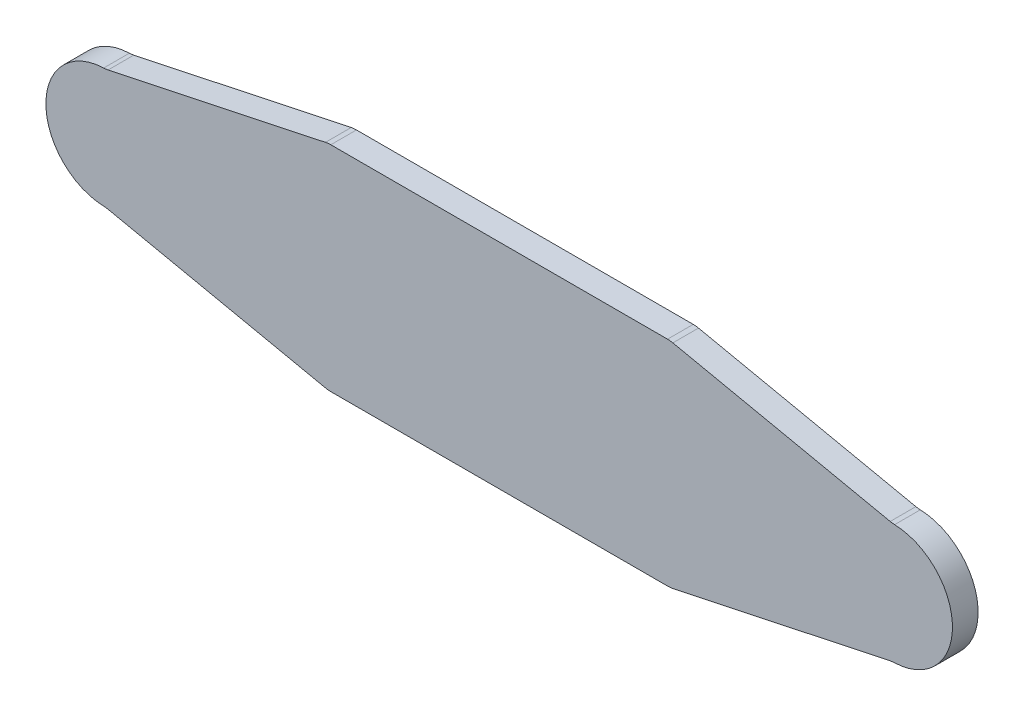
SolidWorks part; units mm, degrees
ref_plane "Front Plane" through (0, 0, 0) normal (0, 0, 1) x (1, 0, 0)
ref_plane "Top Plane" through (0, 0, 0) normal (0, 1, 0) x (1, 0, 0)
ref_plane "Right Plane" through (0, 0, 0) normal (1, 0, 0) x (0, 0, -1)
sketch "Sketch1" plane through (0, 0, 0) normal (0, 0, 1) x (1, 0, 0)
  line L0 (0, 0) -> (40, 0)
  line L1 (0, -25) -> (40, -25)
  line L2 (40, -25) -> (66, -19.5)
  line L3 (40, 0) -> (66, -5.5)
  line L4 (0, 0) -> (-26, -5.5)
  line L5 (0, -25) -> (-26, -19.5)
  arc A0 (-26, -5.5) -> (-26, -19.5) centre (-26, -12.5) ccw
  arc A1 (66, -5.5) -> (66, -19.5) centre (66, -12.5) cw
  dimension "D1" = 26
  dimension "D2" = 7
  dimension "D3" = 40
  dimension "D4" = 26
  dimension "D6" = 25
extrude "Boss-Extrude1" add sketch "Sketch1" along normal blind 3
fillet "Fillet1" radius 3 8 edges at (-26, -19.5, 1.5) (0, -25, 1.5) (40, -25, 1.5) (66, -19.5, 1.5) (66, -5.5, 1.5) (40, 0, 1.5) (0, 0, 1.5) (-26, -5.5, 1.5)
